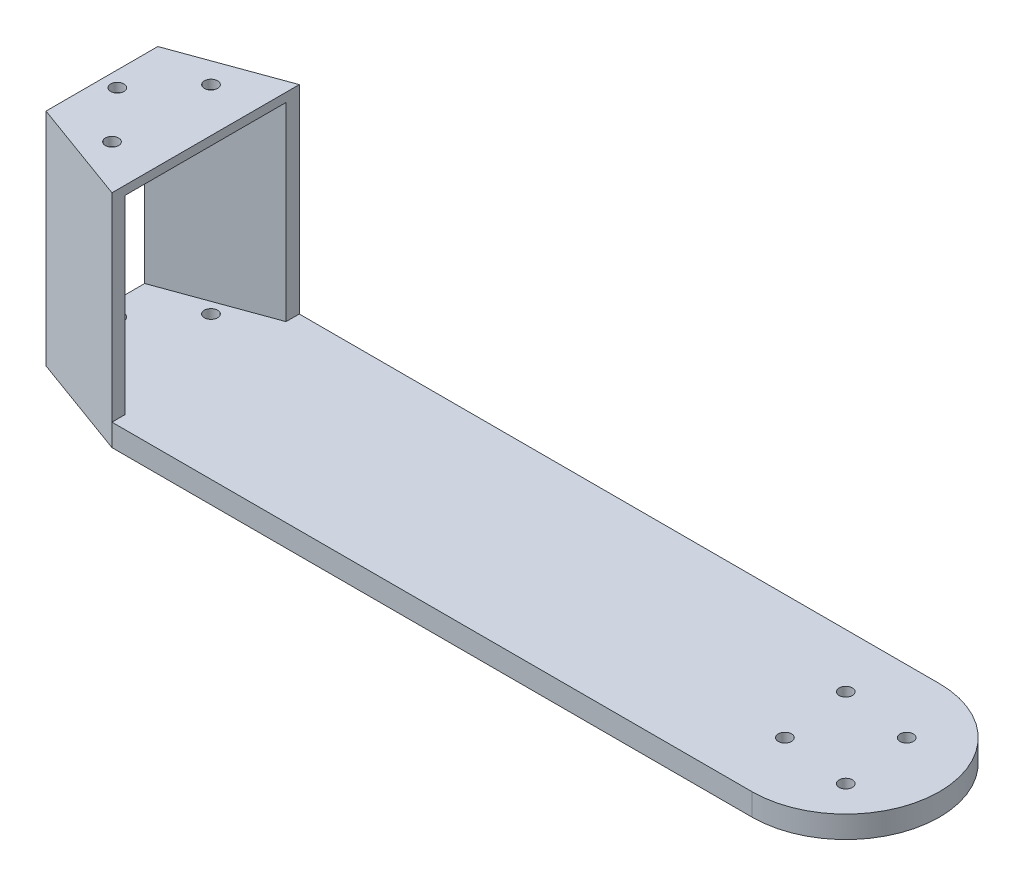
SolidWorks part; units mm, degrees
ref_plane "前视基准面" through (0, 0, 0) normal (0, 0, 1) x (1, 0, 0)
ref_plane "上视基准面" through (0, 0, 0) normal (0, 1, 0) x (1, 0, 0)
ref_plane "右视基准面" through (0, 0, 0) normal (1, 0, 0) x (0, 0, -1)
other "Configuration Table"
sketch "草图1" plane through (0, 0, 0) normal (0, 1, 0) x (1, 0, 0)
  line L6 (72.807, 44.3662) -> (49.3147, 35.8157)
  line L7 (72.807, 1.9362) -> (49.3147, 10.4867)
  line L8 (49.3147, 35.8157) -> (49.3147, 10.4867)
  line L9 (72.807, 44.3662) -> (217.807, 44.3662)
  line L10 (72.807, 1.9362) -> (217.807, 1.9362)
  arc A3 (217.807, 44.3662) -> (217.807, 1.9362) centre (217.807, 23.1512) cw
extrude "凸台-拉伸1" add sketch "草图1" along normal blind 5
sketch "草图3" plane through (0, 0, 0) normal (0, -1, 0) x (1, 0, 0)
  circle A0 centre (226.8227, -14.1356) radius 1.5
  circle A1 centre (224.7013, -30.0455) radius 1.5
  circle A2 centre (208.7914, -32.1668) radius 1.5
  circle A4 centre (210.9128, -16.2569) radius 1.5
extrude "切除-拉伸1" cut sketch "草图3" against normal blind 5
sketch "草图4" plane through (0, 0, 0) normal (0, -1, 0) x (1, 0, 0)
  circle A0 centre (62.807, -11.9362) radius 1.5
  circle A1 centre (52.807, -23.1512) radius 1.5
  circle A2 centre (62.807, -34.3662) radius 1.5
extrude "切除-拉伸2" cut sketch "草图4" against normal blind 50
sketch "草图5" plane through (0, 5, 0) normal (0, 1, 0) x (1, 0, 0)
  line L0 (72.807, 44.3662) -> (72.807, 1.9362)
  line L1 (72.807, 1.9362) -> (49.3147, 10.4867)
  line L2 (49.3147, 10.4867) -> (49.3147, 35.8157)
  line L3 (49.3147, 35.8157) -> (72.807, 44.3662)
extrude "凸台-拉伸2" add sketch "草图5" along normal blind 45
sketch "草图6" plane through (72.807, 0, 0) normal (1, 0, 0) x (0, 0, -1)
  line L1 (44.3662, 5) -> (1.9362, 5) construction
  line L2 (4.9362, 5) -> (4.9362, 48)
  line L5 (4.9362, 48) -> (41.3662, 48)
  line L8 (41.3662, 48) -> (41.3662, 5)
  line L9 (41.3662, 5) -> (4.9362, 5)
sketch "草图7" plane through (49.3147, 0, 0) normal (-1, 0, 0) x (0, 0, 1)
  line L1 (-4.9362, 48) -> (-41.3662, 48) construction
  line L2 (-32.8395, 48) -> (-32.8395, 5)
  line L3 (-41.3662, 5) -> (-4.9362, 5) construction
  line L7 (-13.4867, 5) -> (-32.8395, 5)
  line L8 (-13.4867, 5) -> (-13.4867, 48)
  line L9 (-13.4867, 48) -> (-32.8395, 48)
loft "切除-放样1" cut profiles "草图6", "草图7"
sketch "草图8" plane through (0, 50, 0) normal (0, 1, 0) x (1, 0, 0)
  circle A0 centre (62.807, 34.3662) radius 1.5
  circle A1 centre (52.807, 23.1512) radius 1.5
  circle A2 centre (62.807, 11.9362) radius 1.5
extrude "切除-拉伸3" cut sketch "草图8" against normal blind 45
